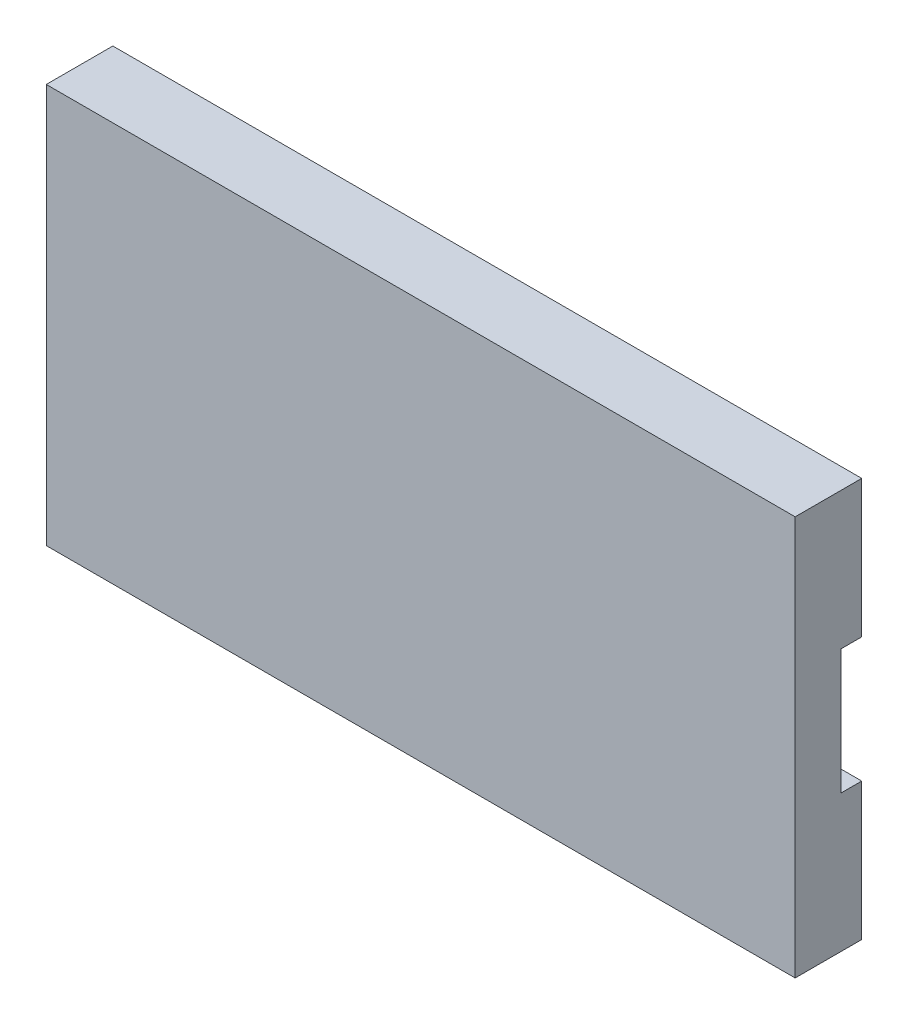
SolidWorks part; units mm, degrees
material "3d打印 35%"
ref_plane "前视基准面" through (0, 0, 0) normal (0, 0, 1) x (1, 0, 0)
ref_plane "上视基准面" through (0, 0, 0) normal (0, 1, 0) x (1, 0, 0)
ref_plane "右视基准面" through (0, 0, 0) normal (1, 0, 0) x (0, 0, -1)
sketch "草图1" plane through (0, 0, 0) normal (0, 0, 1) x (1, 0, 0)
  line L1 (-45, 24) -> (45, 24)
  line L2 (-45, 24) -> (-45, -24)
  line L3 (-45, -24) -> (45, -24)
  line L4 (45, 24) -> (45, -24)
  line L5 (-45, 24) -> (45, -24) construction
  line L6 (-45, -24) -> (45, 24) construction
  point P0 (0, 0)
  dimension "D1" = 90
  dimension "D2" = 48
extrude "凸台-拉伸1" add sketch "草图1" along normal blind 8 contours L1 L4 L3 L2
sketch "草图2" plane through (0, 0, 0) normal (0, 0, -1) x (-1, 0, 0)
  line L1 (-45, 24) -> (-37, 24)
  line L2 (-45, 24) -> (-45, 7.5)
  line L3 (-45, 7.5) -> (-37, 7.5)
  line L4 (-37, 24) -> (-37, 7.5)
ref_plane "基准面4" through (0, 0, 0) normal (1, 0, 0) x (0, 0, -1)
ref_plane "基准面5" through (0, 0, 0) normal (0, 1, 0) x (1, 0, 0)
sketch "草图4" plane through (0, 0, 0) normal (0, 0, -1) x (-1, 0, 0)
  circle A0 centre (0, 0) radius 15
  dimension "D1" = 30
extrude "切除-拉伸3" cut sketch "草图4" against normal blind 3
sketch "草图5" plane through (0, 0, 0) normal (0, 0, -1) x (-1, 0, 0)
  line L0 (-45, 24) -> (-37, 24) construction
  line L1 (-45, 24) -> (-45, 7.5) construction
  circle A0 centre (-41, 21) radius 1.8
  dimension "D1" = 3
  dimension "D2" = 4
extrude "切除-拉伸4" cut sketch "草图5" against normal blind 3
mirror "镜向1" about plane through (0, 0, 0) normal (0, 1, 0) of "切除-拉伸4"
mirror "镜向2" about plane through (0, 0, 0) normal (1, 0, 0) of "镜向1", "切除-拉伸4"
sketch "草图6" plane through (0, 0, 0) normal (0, 0, -1) x (-1, 0, 0)
  line L0 (45, 24) -> (45, -24) construction
  line L1 (53, 7.5) -> (37, 7.5)
  line L2 (53, 7.5) -> (53, -7.5)
  line L3 (53, -7.5) -> (37, -7.5)
  line L4 (37, 7.5) -> (37, -7.5)
  line L5 (53, 7.5) -> (37, -7.5) construction
  line L6 (53, -7.5) -> (37, 7.5) construction
  point P0 (45, 0)
extrude "切除-拉伸5" cut sketch "草图6" against normal blind 2.5
mirror "镜向3" about plane through (0, 0, 0) normal (1, 0, 0) of "切除-拉伸5"
